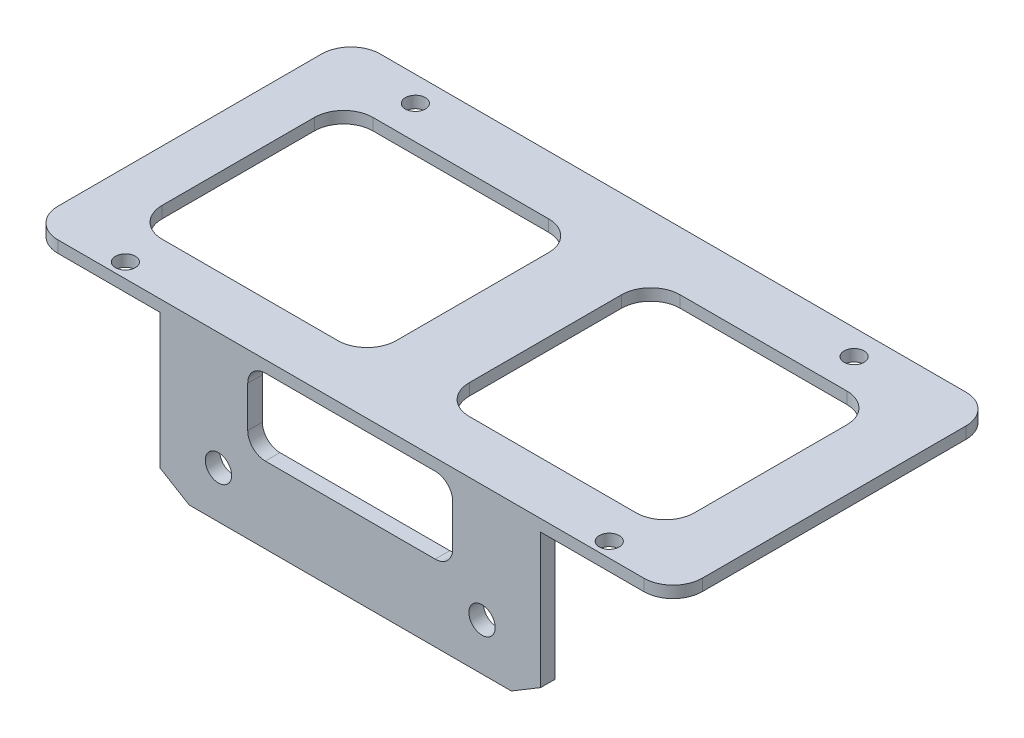
SolidWorks part; units mm, degrees
ref_plane "前视基准面" through (0, 0, 0) normal (0, 0, 1) x (1, 0, 0)
ref_plane "上视基准面" through (0, 0, 0) normal (0, 1, 0) x (1, 0, 0)
ref_plane "右视基准面" through (0, 0, 0) normal (1, 0, 0) x (0, 0, -1)
sketch "草图1" plane through (0, 0, 0) normal (0, 1, 0) x (1, 0, 0)
  line L1 (5, 0) -> (105, 0)
  line L2 (0, 5) -> (0, 50)
  line L3 (5, 55) -> (105, 55)
  line L4 (110, 5) -> (110, 50)
  line L5 (13.7669, 45) -> (43.7502, 45)
  line L6 (8.7669, 40) -> (8.7669, 14)
  line L7 (13.7669, 9) -> (43.7502, 9)
  line L8 (48.7502, 40) -> (48.7502, 14)
  line L9 (66.2018, 45) -> (94.6633, 45)
  line L10 (61.2018, 40) -> (61.2018, 14)
  line L11 (66.2018, 9) -> (94.6633, 9)
  line L12 (99.6633, 40) -> (99.6633, 14)
  arc A0 (0, 5) -> (5, 0) centre (5, 5) ccw
  arc A1 (105, 0) -> (110, 5) centre (105, 5) ccw
  arc A2 (110, 50) -> (105, 55) centre (105, 50) ccw
  arc A3 (5, 55) -> (0, 50) centre (5, 50) ccw
  circle A4 centre (14, 2.5) radius 1.7
  circle A5 centre (15.3, 50.7) radius 1.7
  circle A6 centre (90.2, 50.7) radius 1.7
  circle A7 centre (96.6, 2.5) radius 1.7
  arc A8 (61.2018, 14) -> (66.2018, 9) centre (66.2018, 14) ccw
  arc A9 (94.6633, 9) -> (99.6633, 14) centre (94.6633, 14) ccw
  arc A10 (99.6633, 40) -> (94.6633, 45) centre (94.6633, 40) ccw
  arc A11 (66.2018, 45) -> (61.2018, 40) centre (66.2018, 40) ccw
  arc A12 (43.7502, 45) -> (48.7502, 40) centre (43.7502, 40) cw
  arc A13 (48.7502, 14) -> (43.7502, 9) centre (43.7502, 14) cw
  arc A14 (13.7669, 9) -> (8.7669, 14) centre (13.7669, 14) cw
  arc A15 (8.7669, 40) -> (13.7669, 45) centre (13.7669, 40) cw
  point P7 (0, 0)
  dimension "D1" = 5
  dimension "D3" = 3.4
  dimension "D5" = 3.4
  dimension "D9" = 3.4
  dimension "D12" = 3.4
  dimension "D13" = 5
  dimension "D2" = 2.5
  dimension "D4" = 14
  dimension "D6" = 1.3
  dimension "D7" = 50.7
  dimension "D8" = 74.9
  dimension "D10" = 50.7
  dimension "D11" = 96.6
  dimension "D14" = 26
  dimension "D15" = 26
extrude "凸台-拉伸2" add sketch "草图1" along normal blind 2
sketch "草图2" plane through (0, 0, 0) normal (0, -1, 0) x (1, 0, 0)
  line L0 (5, 0) -> (105, 0) construction
  line L1 (22.3833, 0) -> (87.3833, 0)
  line L2 (22.3833, 0) -> (22.3833, -2.5)
  line L3 (22.3833, -2.5) -> (87.3833, -2.5)
  line L4 (87.3833, 0) -> (87.3833, -2.5)
  dimension "D1" = 2.5
  dimension "D2" = 65
extrude "凸台-拉伸3" add sketch "草图2" along normal blind 30
sketch "草图3" plane through (0, 0, 0) normal (0, 0, 1) x (1, 0, 0)
  line L0 (5, 2) -> (105, 2) construction
  line L1 (22.3833, -30) -> (22.3833, 0) construction
  line L2 (87.3833, -30) -> (87.3833, 0) construction
  line L3 (87.3833, -30) -> (87.3833, -23)
  line L4 (87.3833, -23) -> (82.3833, -26)
  line L6 (82.3833, -26) -> (27.3833, -26)
  line L7 (27.3833, -26) -> (22.3833, -23)
  line L8 (22.3833, -23) -> (22.3833, -30)
  line L9 (87.3833, -30) -> (22.3833, -30) construction
  line L10 (22.3833, -30) -> (87.3833, -30)
  line L11 (69.3833, -13) -> (40.3833, -13)
  line L12 (72.3833, -10) -> (72.3833, -3)
  line L13 (69.3833, 0) -> (40.3833, 0)
  line L14 (37.3833, -10) -> (37.3833, -3)
  circle A0 centre (77.3833, -18) radius 2.25
  circle A1 centre (32.3833, -18) radius 2.25
  arc A2 (40.3833, 0) -> (37.3833, -3) centre (40.3833, -3) ccw
  arc A3 (69.3833, 0) -> (72.3833, -3) centre (69.3833, -3) cw
  arc A4 (69.3833, -13) -> (72.3833, -10) centre (69.3833, -10) ccw
  arc A5 (40.3833, -13) -> (37.3833, -10) centre (40.3833, -10) cw
  dimension "D1" = 4.5
  dimension "D2" = 4.5
  dimension "D16" = 3
  dimension "D17" = 3
  dimension "D3" = 20
  dimension "D4" = 20
  dimension "D5" = 10
  dimension "D6" = 10
  dimension "D7" = 5
  dimension "D8" = 5
  dimension "D9" = 7
  dimension "D10" = 7
  dimension "D11" = 15
  dimension "D12" = 15
  dimension "D13" = 2
  dimension "D14" = 15
  dimension "D15" = 3
extrude "切除-拉伸1" cut sketch "草图3" against normal blind 2.5
equation "\"4nn\"=10.289"
